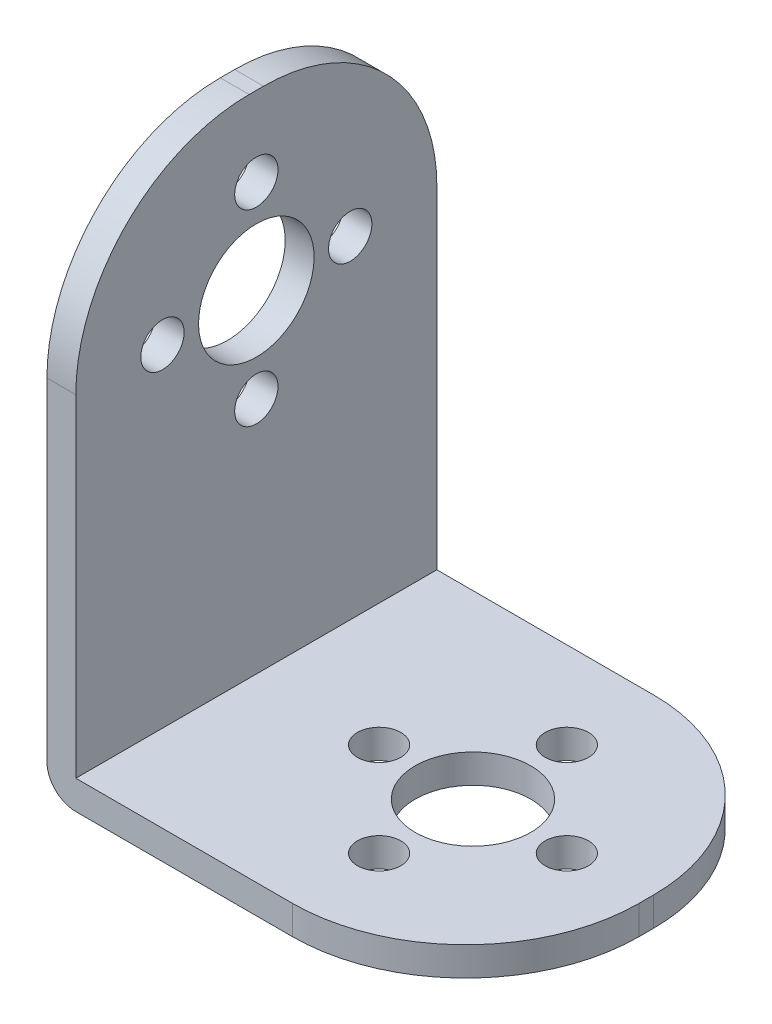
SolidWorks part; units mm, degrees
ref_plane "Front Plane" through (0, 0, 0) normal (0, 0, 1) x (1, 0, 0)
ref_plane "Top Plane" through (0, 0, 0) normal (0, 1, 0) x (1, 0, 0)
ref_plane "Right Plane" through (0, 0, 0) normal (1, 0, 0) x (0, 0, -1)
sketch "Sketch1" plane through (0, 0, 0) normal (0, 1, 0) x (1, 0, 0)
  line L1 (0, 0) -> (29, 0)
  line L2 (0, 0) -> (0, 25)
  line L3 (0, 25) -> (29, 25)
  line L4 (29, 0) -> (29, 25)
  dimension "D1" = 29
  dimension "D2" = 25
extrude "Boss-Extrude1" add sketch "Sketch1" along normal blind 37
sketch "Sketch2" plane through (0, 0, 0) normal (0, 0, 1) x (1, 0, 0)
  line L0 (0, 37) -> (29, 37) construction
  line L1 (2, 37) -> (29, 37)
  line L2 (2, 37) -> (2, 2)
  line L3 (2, 2) -> (29, 2)
  line L4 (29, 37) -> (29, 2)
  line L5 (29, 37) -> (29, 0) construction
  line L6 (0, 37) -> (0, 0) construction
  line L7 (0, 0) -> (29, 0) construction
  dimension "D1" = 2
  dimension "D2" = 2
extrude "Cut-Extrude1" cut sketch "Sketch2" against normal blind 37
fillet "Fillet1" radius 2 1 edges at (0, 0, -12.5)
sketch "Sketch3" plane through (0, 2, 0) normal (0, 1, 0) x (1, 0, 0)
  line L0 (29, 25) -> (29, 0) construction
  line L1 (2, 25) -> (29, 25) construction
  line L3 (10.5, 12.5) -> (17, 12.5) construction
  circle A0 centre (23.5, 12.5) radius 1.5
  circle A1 centre (17, 12.5) radius 4
  circle A2 centre (10.5, 12.5) radius 1.5
  circle A3 centre (17, 19) radius 1.5
  circle A5 centre (17, 6) radius 1.5
  dimension "D1" = 3
  dimension "D3" = 3
  dimension "D4" = 3
  dimension "D5" = 6.5
  dimension "D8" = 6.5
  dimension "D6" = 6
  dimension "D11" = 8
  dimension "D2" = 5.5
  dimension "D7" = 6.5
  dimension "D9" = 0
  dimension "D10" = 0
extrude "Cut-Extrude2" cut sketch "Sketch3" against normal through all
fillet "Fillet3" radius 12 2 edges at (29, 1, 0) (29, 1, -25)
fillet "Fillet4" radius 12 2 edges at (1, 37, -25) (1, 37, 0)
sketch "Sketch5" plane through (2, 0, 0) normal (1, 0, 0) x (0, 0, -1)
  line L0 (12.5, 37) -> (12.5, 19.7337) construction
  line L1 (12, 37) -> (13, 37) construction
  circle A0 centre (12.5, 31.5) radius 1.5
  circle A1 centre (12.5, 25) radius 4
  circle A2 centre (6, 25) radius 1.5
  circle A3 centre (19, 25) radius 1.5
  circle A4 centre (12.5, 18.5) radius 1.5
  dimension "D1" = 8
  dimension "D2" = 3
  dimension "D5" = 3
  dimension "D6" = 6.5
  dimension "D7" = 3
  dimension "D3" = 6.5
  dimension "D4" = 5.5
  dimension "D8" = 6.5
extrude "Cut-Extrude3" cut sketch "Sketch5" against normal through all
